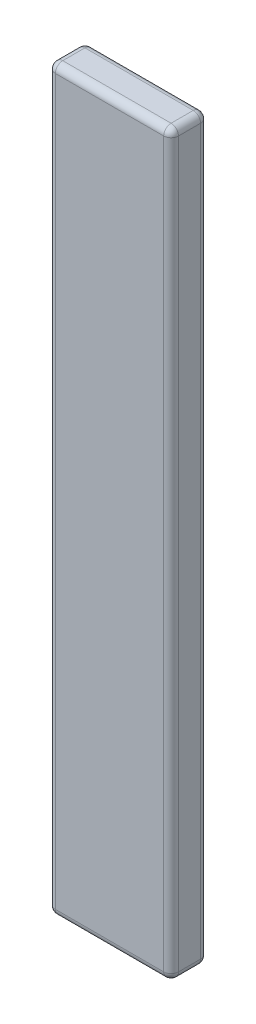
SolidWorks part; units mm, degrees
ref_plane "Ebene vorne" through (0, 0, 0) normal (0, 0, 1) x (1, 0, 0)
ref_plane "Ebene oben" through (0, 0, 0) normal (0, 1, 0) x (1, 0, 0)
ref_plane "Ebene rechts" through (0, 0, 0) normal (1, 0, 0) x (0, 0, -1)
sketch "Skizze1" plane through (0, 0, 0) normal (0, 0, 1) x (1, 0, 0)
  line L1 (0, 0) -> (10, 0)
  line L2 (0, 0) -> (0, -60)
  line L3 (0, -60) -> (10, -60)
  line L4 (10, 0) -> (10, -60)
  dimension "D1" = 60
  dimension "D2" = 10
extrude "Aufsatz-Linear austragen1" add sketch "Skizze1" along normal blind 3
fillet "Verrundung1" radius 0.6 12 edges at (0, -60, 1.5) (0, -30, 0) (5, -60, 0) (10, -30, 0) (10, -60, 1.5) (0, 0, 1.5) (5, 0, 0) (10, 0, 1.5) (5, -60, 3) (5, 0, 3) (0, -30, 3) (10, -30, 3)
